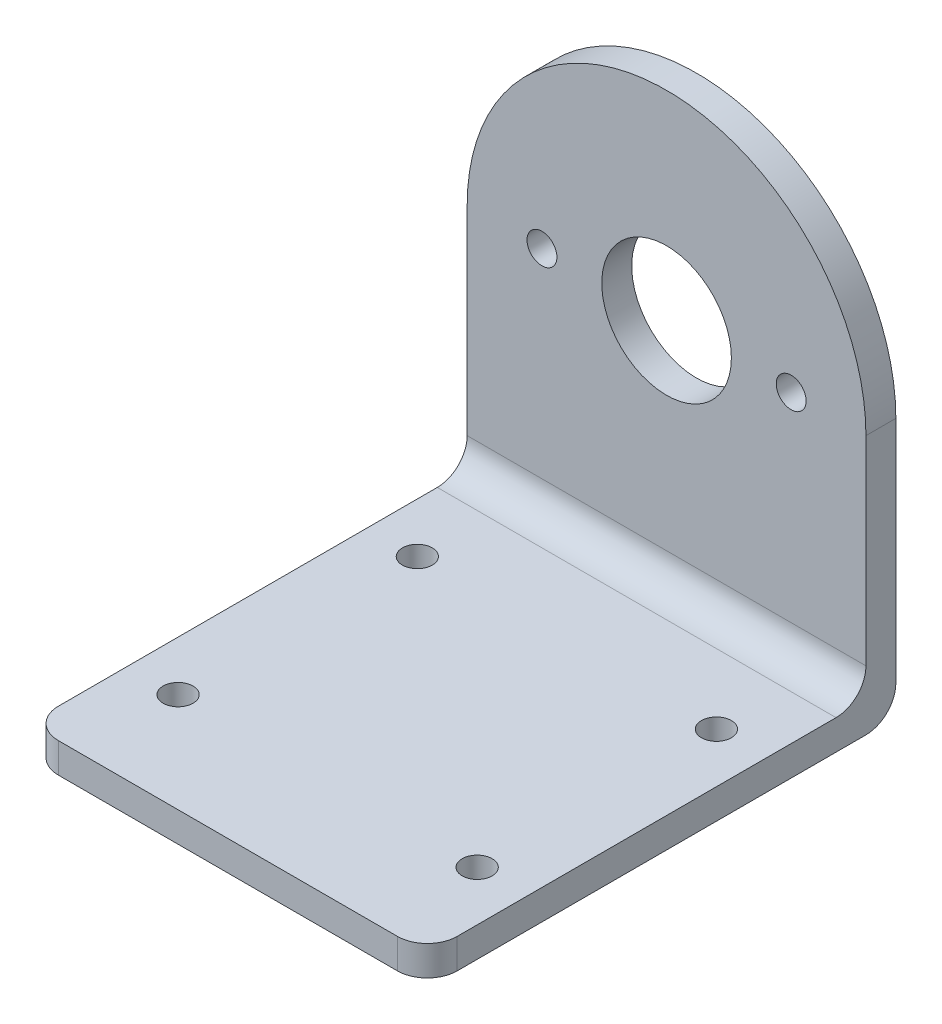
SolidWorks part; units mm, degrees
ref_plane "Спереди" through (0, 0, 0) normal (0, 0, 1) x (1, 0, 0)
ref_plane "Сверху" through (0, 0, 0) normal (0, 1, 0) x (1, 0, 0)
ref_plane "Справа" through (0, 0, 0) normal (1, 0, 0) x (0, 0, -1)
sketch "Эскиз1" plane through (0, 0, 0) normal (0, 0, 1) x (1, 0, 0)
  line L0 (-7.2365, 26) -> (46.7607, 26) construction
  line L1 (0, 0) -> (40, 0)
  line L2 (0, 0) -> (0, 26)
  line L4 (40, 0) -> (40, 26)
  circle A0 centre (20, 26) radius 6.5
  arc A1 (40, 26) -> (0, 26) centre (20, 26) ccw
  circle A2 centre (32.5, 26) radius 1.5
  circle A3 centre (7.5, 26) radius 1.5
extrude "Бобышка-Вытянуть1" add sketch "Эскиз1" along normal blind 3
sketch "Эскиз2" plane through (0, 0, 3) normal (0, 0, 1) x (1, 0, 0)
  line L0 (40, 0) -> (40, 26) construction
  line L1 (0, 0) -> (40, 0)
  line L2 (0, 0) -> (0, 3)
  line L3 (0, 3) -> (40, 3)
  line L4 (40, 0) -> (40, 3)
  dimension "D1" = 3
extrude "Бобышка-Вытянуть2" add sketch "Эскиз2" along normal blind 44
fillet "Скругление4" radius 3 1 edges at (20, 0, 0)
sketch "Эскиз3" plane through (0, 0, 0) normal (0, -1, 0) x (1, 0, 0)
  line L1 (0, 47) -> (40, 47) construction
  line L2 (35, 47) -> (35, 3) construction
  line L3 (0, 3) -> (40, 3) construction
  line L5 (5, 47) -> (5, 3) construction
  circle A0 centre (5, 37) radius 1.5
  circle A1 centre (35, 37) radius 1.5
  circle A2 centre (5, 13) radius 1.5
  circle A3 centre (35, 13) radius 1.5
extrude "Вырез-Вытянуть1" cut sketch "Эскиз3" against normal through all
fillet "Скругление5" radius 3 1 edges
fillet "Скругление6" radius 3 2 edges at (40, 1.5, 47) (0, 1.5, 47)
